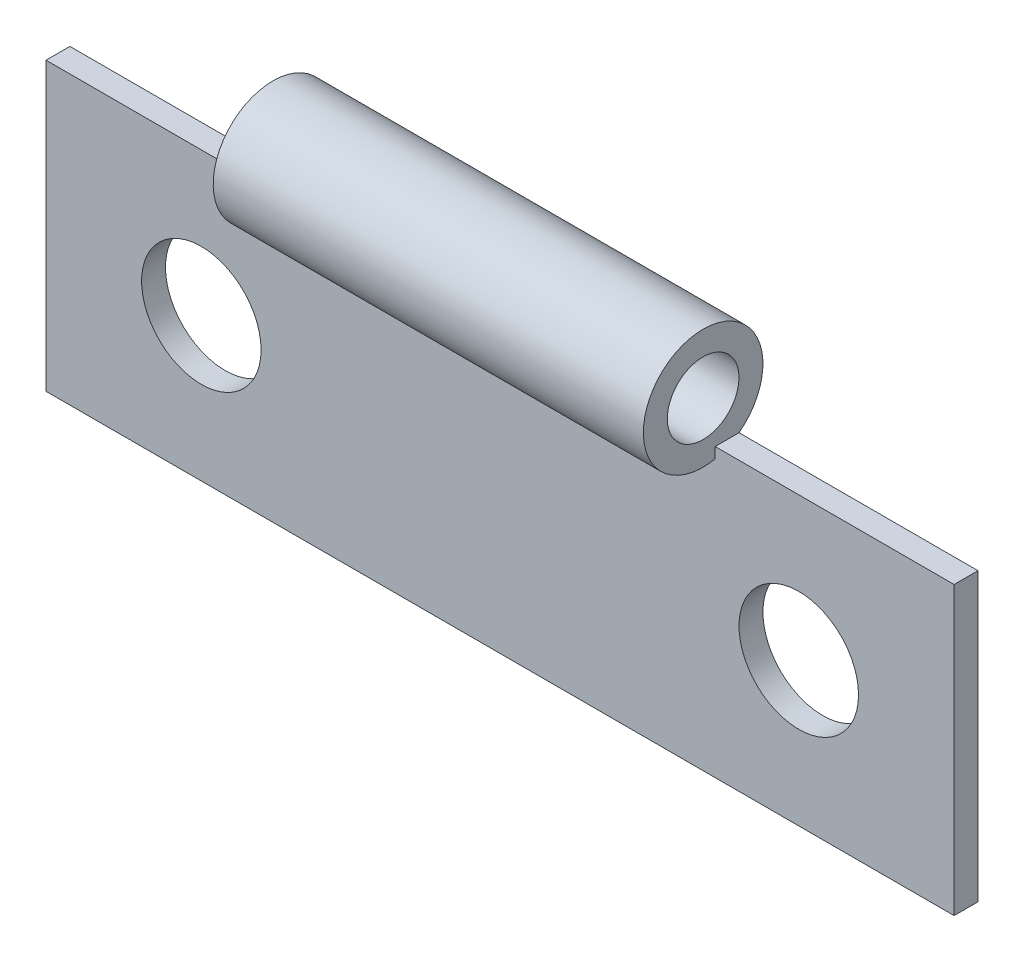
SolidWorks part; units mm, degrees
ref_plane "Front" through (0, 0, 0) normal (0, 0, 1) x (1, 0, 0)
ref_plane "Top" through (0, 0, 0) normal (0, 1, 0) x (1, 0, 0)
ref_plane "Right" through (0, 0, 0) normal (1, 0, 0) x (0, 0, -1)
sketch "草图1" plane through (0, 0, 0) normal (0, 0, 1) x (1, 0, 0)
  line L1 (-19, -6) -> (19, -6)
  line L2 (-19, -6) -> (-19, 6)
  line L3 (-19, 6) -> (19, 6)
  line L4 (19, -6) -> (19, 6)
  line L5 (-19, -6) -> (19, 6) construction
  line L6 (-19, 6) -> (19, -6) construction
  circle A0 centre (12.5, 0) radius 2.5
  circle A1 centre (-12.5, 0) radius 2.5
  point P0 (0, 0)
  dimension "D1" = 12
  dimension "D2" = 38
extrude "凸台-拉伸1" add sketch "草图1" along normal blind 1
ref_plane "基准面1" through (-9, 0, 0) normal (-1, 0, 0) x (0, 0, 1)
sketch "草图3" plane through (-9, 0, 0) normal (-1, 0, 0) x (0, 0, 1)
  circle A0 centre (1.5018, 8.0018) radius 2.5018
  circle A1 centre (1.5018, 8.0018) radius 1.5
extrude "凸台-拉伸2" add sketch "草图3" against normal blind 18
move or copy body "实体-移动/复制1" [suppressed] bodies to move or copy 102
